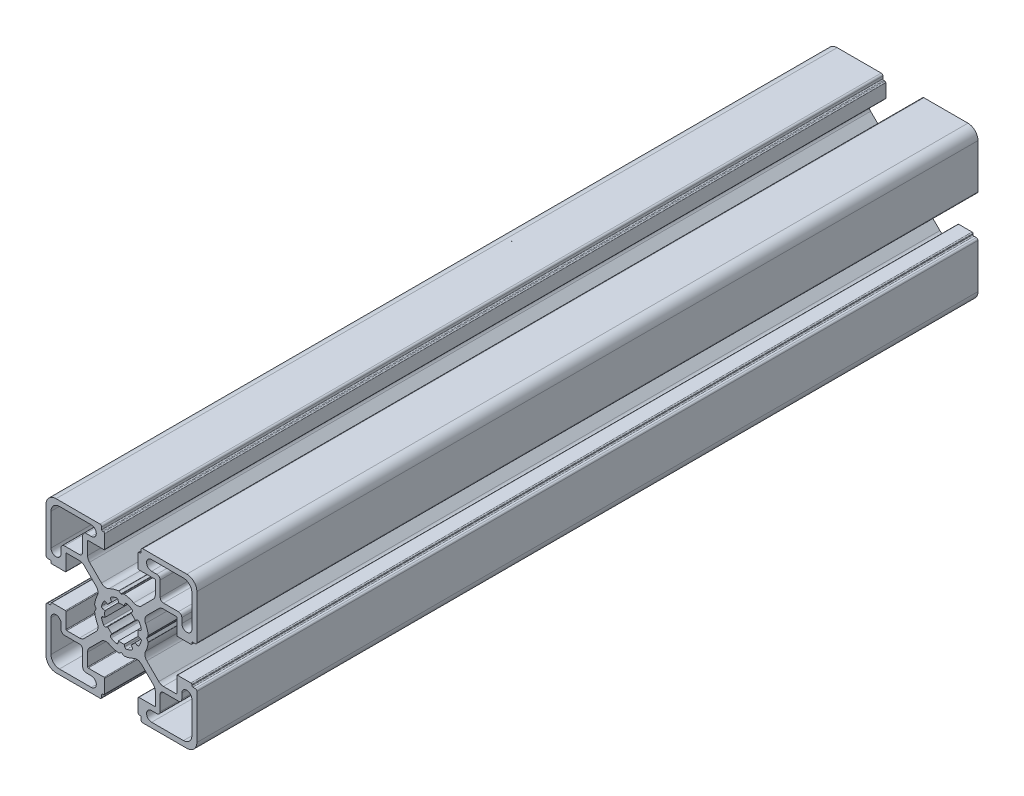
SolidWorks part; units mm, degrees
ref_plane "Front Plane" through (0, 0, 0) normal (0, 0, 1) x (1, 0, 0)
ref_plane "Top Plane" through (0, 0, 0) normal (0, 1, 0) x (1, 0, 0)
ref_plane "Right Plane" through (0, 0, 0) normal (1, 0, 0) x (0, 0, -1)
sketch "Sketch1" plane through (0, 0, 0) normal (0, 0, 1) x (1, 0, 0)
  line L0 (10.55, 18) -> (9, 18)
  line L1 (18.5, 21) -> (9, 21)
  line L2 (21, 9.0002) -> (21, 18.5)
  line L3 (18, 9.0002) -> (18, 10.55)
  line L4 (17, 11.55) -> (12.55, 11.55)
  line L5 (11.55, 12.55) -> (11.55, 17)
  line L6 (7.974, 0.7926) -> (7.5401, 0.0468)
  line L7 (-0.8674, 4.9242) -> (-0.9675, 5.4811)
  line L8 (-3.1913, 4.5626) -> (-2.864, 4.0985)
  line L9 (-4.0897, 2.8765) -> (-4.5668, 3.2082)
  line L10 (-5.4897, 0.9862) -> (-4.9205, 0.8878)
  line L11 (11.1298, 9.425) -> (7.5635, 5.8587)
  line L12 (16.3169, 9.9945) -> (12.5048, 9.9945)
  line L13 (16.5169, 5.2) -> (16.5169, 9.7945)
  line L14 (20.7196, 5) -> (16.7169, 5)
  line L15 (21.0196, 5.3) -> (21.0196, 5.5)
  line L16 (22, 5.8) -> (21.3196, 5.8)
  line L17 (22.5, 6.3) -> (22.5, 19.5)
  line L18 (19.5, 22.5) -> (6.3757, 22.5)
  line L19 (5.8757, 21.3) -> (5.8757, 22)
  line L20 (5.5757, 21) -> (5.3, 21)
  line L21 (5, 16.6668) -> (5, 20.7)
  line L22 (9.9054, 16.4668) -> (5.2, 16.4668)
  line L23 (10.1054, 12.4716) -> (10.1054, 16.2668)
  line L24 (5.9449, 7.4827) -> (9.5196, 11.0574)
  line L25 (0.1126, 7.6069) -> (0.7547, 7.9748)
  line L26 (5.4897, 0.9862) -> (4.9205, 0.8878)
  line L27 (4.0897, 2.8765) -> (4.5668, 3.2082)
  line L28 (3.1913, 4.5626) -> (2.864, 4.0985)
  line L29 (0.8674, 4.9242) -> (0.9675, 5.4811)
  line L30 (-10.55, -18) -> (-9, -18)
  line L31 (-18.5, -21) -> (-9, -21)
  line L32 (-21, -9.0002) -> (-21, -18.5)
  line L33 (-18, -9.0002) -> (-18, -10.55)
  line L34 (-17, -11.55) -> (-12.55, -11.55)
  line L35 (-11.55, -12.55) -> (-11.55, -17)
  line L36 (-7.974, -0.7926) -> (-7.5401, -0.0468)
  line L37 (-11.1298, -9.425) -> (-7.5635, -5.8587)
  line L38 (-16.3169, -9.9945) -> (-12.5048, -9.9945)
  line L39 (-16.5169, -5.2) -> (-16.5169, -9.7945)
  line L40 (-20.7196, -5) -> (-16.7169, -5)
  line L41 (-21.0196, -5.3) -> (-21.0196, -5.5)
  line L42 (-22, -5.8) -> (-21.3196, -5.8)
  line L43 (-22.5, -6.3) -> (-22.5, -19.5)
  line L44 (-19.5, -22.5) -> (-6.3757, -22.5)
  line L45 (-5.8757, -21.3) -> (-5.8757, -22)
  line L46 (-5.5757, -21) -> (-5.3, -21)
  line L47 (-5, -16.6668) -> (-5, -20.7)
  line L48 (-9.9054, -16.4668) -> (-5.2, -16.4668)
  line L49 (-10.1054, -12.4716) -> (-10.1054, -16.2668)
  line L50 (-5.9449, -7.4827) -> (-9.5196, -11.0574)
  line L51 (-0.1126, -7.6069) -> (-0.7547, -7.9748)
  line L52 (0.8674, -4.9242) -> (0.9675, -5.4811)
  line L53 (3.1913, -4.5626) -> (2.864, -4.0985)
  line L54 (4.0897, -2.8765) -> (4.5668, -3.2082)
  line L55 (5.4897, -0.9862) -> (4.9205, -0.8878)
  line L56 (0.1126, -7.6069) -> (0.7547, -7.9748)
  line L57 (5.9449, -7.4827) -> (9.5196, -11.0574)
  line L58 (10.1054, -12.4716) -> (10.1054, -16.2668)
  line L59 (9.9054, -16.4668) -> (5.2, -16.4668)
  line L60 (5, -16.6668) -> (5, -20.7)
  line L61 (5.5757, -21) -> (5.3, -21)
  line L62 (-0.1126, 7.6069) -> (-0.7547, 7.9748)
  line L63 (-5.9449, 7.4827) -> (-9.5196, 11.0574)
  line L64 (-10.1054, 12.4716) -> (-10.1054, 16.2668)
  line L65 (-9.9054, 16.4668) -> (-5.2, 16.4668)
  line L66 (-5, 16.6668) -> (-5, 20.7)
  line L67 (-5.5757, 21) -> (-5.3, 21)
  line L68 (-5.8757, 21.3) -> (-5.8757, 22)
  line L69 (-19.5, 22.5) -> (-6.3757, 22.5)
  line L70 (-22.5, 6.3) -> (-22.5, 19.5)
  line L71 (-22, 5.8) -> (-21.3196, 5.8)
  line L72 (-21.0196, 5.3) -> (-21.0196, 5.5)
  line L73 (-20.7196, 5) -> (-16.7169, 5)
  line L74 (-16.5169, 5.2) -> (-16.5169, 9.7945)
  line L75 (-16.3169, 9.9945) -> (-12.5048, 9.9945)
  line L76 (-11.1298, 9.425) -> (-7.5635, 5.8587)
  line L77 (-7.974, 0.7926) -> (-7.5401, 0.0468)
  line L78 (5.8757, -21.3) -> (5.8757, -22)
  line L79 (19.5, -22.5) -> (6.3757, -22.5)
  line L80 (22.5, -6.3) -> (22.5, -19.5)
  line L81 (22, -5.8) -> (21.3196, -5.8)
  line L82 (21.0196, -5.3) -> (21.0196, -5.5)
  line L83 (20.7196, -5) -> (16.7169, -5)
  line L84 (16.5169, -5.2) -> (16.5169, -9.7945)
  line L85 (16.3169, -9.9945) -> (12.5048, -9.9945)
  line L86 (11.1298, -9.425) -> (7.5635, -5.8587)
  line L87 (-5.4897, -0.9862) -> (-4.9205, -0.8878)
  line L88 (-4.0897, -2.8765) -> (-4.5668, -3.2082)
  line L89 (-3.1913, -4.5626) -> (-2.864, -4.0985)
  line L90 (-0.8674, -4.9242) -> (-0.9675, -5.4811)
  line L91 (7.974, -0.7926) -> (7.5401, -0.0468)
  line L92 (-11.55, 12.55) -> (-11.55, 17)
  line L93 (-17, 11.55) -> (-12.55, 11.55)
  line L94 (-18, 9.0002) -> (-18, 10.55)
  line L95 (-21, 9.0002) -> (-21, 18.5)
  line L96 (-18.5, 21) -> (-9, 21)
  line L97 (-10.55, 18) -> (-9, 18)
  line L98 (11.55, -12.55) -> (11.55, -17)
  line L99 (17, -11.55) -> (12.55, -11.55)
  line L100 (18, -9.0002) -> (18, -10.55)
  line L101 (21, -9.0002) -> (21, -18.5)
  line L102 (18.5, -21) -> (9, -21)
  line L103 (10.55, -18) -> (9, -18)
  line L104 (-33.3633, 0) -> (37.7265, 0) construction
  line L105 (0, 32.2957) -> (0, -36.0465) construction
  arc A0 (9, 18) -> (9, 21) centre (9, 19.5) cw
  arc A1 (18.5, 21) -> (21, 18.5) centre (18.5, 18.5) cw
  arc A2 (21, 9.0002) -> (18, 9.0002) centre (19.5, 9.0002) cw
  arc A3 (17, 11.55) -> (18, 10.55) centre (17, 10.55) cw
  arc A4 (12.55, 11.55) -> (11.55, 12.55) centre (12.55, 12.55) cw
  arc A5 (10.55, 18) -> (11.55, 17) centre (10.55, 17) cw
  arc A6 (7.5313, 0) -> (7.5401, 0.0468) centre (7.7309, -0.013) cw
  arc A7 (8, 0.9141) -> (7.974, 0.7926) centre (7.8011, 0.8932) cw
  arc A8 (7.2004, 3.6119) -> (8, 0.9141) centre (0.0496, 0.0249) cw
  arc A9 (7.2004, 3.6119) -> (7.5635, 5.8587) centre (8.9385, 4.4837) cw
  arc A10 (11.1298, 9.425) -> (12.5048, 9.9945) centre (12.5048, 8.05) cw
  arc A11 (16.3169, 9.9945) -> (16.5169, 9.7945) centre (16.3169, 9.7945) cw
  arc A12 (16.7169, 5) -> (16.5169, 5.2) centre (16.7169, 5.2) cw
  arc A13 (21.0196, 5.3) -> (20.7196, 5) centre (20.7196, 5.3) cw
  arc A14 (0.8674, 4.9242) -> (-0.8674, 4.9242) centre (0, 0) ccw
  arc A15 (-0.9675, 5.4811) -> (-1.5951, 5.8941) centre (-1.4627, 5.4119) ccw
  arc A16 (-1.5951, 5.8941) -> (-3.0444, 5.2994) centre (-0.0235, 0) ccw
  arc A17 (-3.0444, 5.2994) -> (-3.1913, 4.5626) centre (-2.7943, 4.8665) ccw
  arc A18 (-2.864, 4.0985) -> (-4.0897, 2.8765) centre (0, 0) ccw
  arc A19 (-4.5668, 3.2082) -> (-5.3025, 3.0565) centre (-4.868, 2.8091) ccw
  arc A20 (-5.3025, 3.0565) -> (-5.9068, 1.6112) centre (-0.0235, 0) ccw
  arc A21 (-5.9068, 1.6112) -> (-5.4897, 0.9862) centre (-5.4239, 1.4819) ccw
  arc A22 (-4.9205, 0.8878) -> (-5, 0) centre (0, 0) ccw
  arc A23 (21.0196, 5.5) -> (21.3196, 5.8) centre (21.3196, 5.5) cw
  arc A24 (22.5, 6.3) -> (22, 5.8) centre (22, 6.3) cw
  arc A25 (19.5, 22.5) -> (22.5, 19.5) centre (19.5, 19.5) cw
  arc A26 (5.8757, 22) -> (6.3757, 22.5) centre (6.3757, 22) cw
  arc A27 (5.8757, 21.3) -> (5.5757, 21) centre (5.5757, 21.3) cw
  arc A28 (5, 20.7) -> (5.3, 21) centre (5.3, 20.7) cw
  arc A29 (5.2, 16.4668) -> (5, 16.6668) centre (5.2, 16.6668) cw
  arc A30 (9.9054, 16.4668) -> (10.1054, 16.2668) centre (9.9054, 16.2668) cw
  arc A31 (10.1054, 12.4716) -> (9.5196, 11.0574) centre (8.1054, 12.4716) cw
  arc A32 (5.9449, 7.4827) -> (3.6665, 7.1733) centre (4.5855, 8.9496) cw
  arc A33 (0.8764, 8) -> (3.6665, 7.1733) centre (0.0235, 0) cw
  arc A34 (0.7547, 7.9748) -> (0.8764, 8) centre (0.8542, 7.8013) cw
  arc A35 (0.1126, 7.6069) -> (0, 7.531) centre (-0.0489, 7.7249) cw
  arc A36 (4.9205, 0.8878) -> (5, 0) centre (0, 0) cw
  arc A37 (5.9068, 1.6112) -> (5.4897, 0.9862) centre (5.4239, 1.4819) cw
  arc A38 (5.3025, 3.0565) -> (5.9068, 1.6112) centre (0.0235, 0) cw
  arc A39 (4.5668, 3.2082) -> (5.3025, 3.0565) centre (4.868, 2.8091) cw
  arc A40 (2.864, 4.0985) -> (4.0897, 2.8765) centre (0, 0) cw
  arc A41 (3.0444, 5.2994) -> (3.1913, 4.5626) centre (2.7943, 4.8665) cw
  arc A42 (1.5951, 5.8941) -> (3.0444, 5.2994) centre (0.0235, 0) cw
  arc A43 (0.9675, 5.4811) -> (1.5951, 5.8941) centre (1.4627, 5.4119) cw
  arc A44 (-9, -18) -> (-9, -21) centre (-9, -19.5) cw
  arc A45 (-18.5, -21) -> (-21, -18.5) centre (-18.5, -18.5) cw
  arc A46 (-21, -9.0002) -> (-18, -9.0002) centre (-19.5, -9.0002) cw
  arc A47 (-17, -11.55) -> (-18, -10.55) centre (-17, -10.55) cw
  arc A48 (-12.55, -11.55) -> (-11.55, -12.55) centre (-12.55, -12.55) cw
  arc A49 (-10.55, -18) -> (-11.55, -17) centre (-10.55, -17) cw
  arc A50 (-7.5313, 0) -> (-7.5401, -0.0468) centre (-7.7309, 0.013) cw
  arc A51 (-8, -0.9141) -> (-7.974, -0.7926) centre (-7.8011, -0.8932) cw
  arc A52 (-7.2004, -3.6119) -> (-8, -0.9141) centre (-0.0496, -0.0249) cw
  arc A53 (-7.2004, -3.6119) -> (-7.5635, -5.8587) centre (-8.9385, -4.4837) cw
  arc A54 (-11.1298, -9.425) -> (-12.5048, -9.9945) centre (-12.5048, -8.05) cw
  arc A55 (-16.3169, -9.9945) -> (-16.5169, -9.7945) centre (-16.3169, -9.7945) cw
  arc A56 (-16.7169, -5) -> (-16.5169, -5.2) centre (-16.7169, -5.2) cw
  arc A57 (-21.0196, -5.3) -> (-20.7196, -5) centre (-20.7196, -5.3) cw
  arc A58 (-21.0196, -5.5) -> (-21.3196, -5.8) centre (-21.3196, -5.5) cw
  arc A59 (-22.5, -6.3) -> (-22, -5.8) centre (-22, -6.3) cw
  arc A60 (-19.5, -22.5) -> (-22.5, -19.5) centre (-19.5, -19.5) cw
  arc A61 (-5.8757, -22) -> (-6.3757, -22.5) centre (-6.3757, -22) cw
  arc A62 (-5.8757, -21.3) -> (-5.5757, -21) centre (-5.5757, -21.3) cw
  arc A63 (-5, -20.7) -> (-5.3, -21) centre (-5.3, -20.7) cw
  arc A64 (-5.2, -16.4668) -> (-5, -16.6668) centre (-5.2, -16.6668) cw
  arc A65 (-9.9054, -16.4668) -> (-10.1054, -16.2668) centre (-9.9054, -16.2668) cw
  arc A66 (-10.1054, -12.4716) -> (-9.5196, -11.0574) centre (-8.1054, -12.4716) cw
  arc A67 (-5.9449, -7.4827) -> (-3.6665, -7.1733) centre (-4.5855, -8.9496) cw
  arc A68 (-0.8764, -8) -> (-3.6665, -7.1733) centre (-0.0235, 0) cw
  arc A69 (-0.7547, -7.9748) -> (-0.8764, -8) centre (-0.8542, -7.8013) cw
  arc A70 (-0.1126, -7.6069) -> (0, -7.531) centre (0.0489, -7.7249) cw
  arc A71 (0.9675, -5.4811) -> (1.5951, -5.8941) centre (1.4627, -5.4119) ccw
  arc A72 (1.5951, -5.8941) -> (3.0444, -5.2994) centre (0.0235, 0) ccw
  arc A73 (3.0444, -5.2994) -> (3.1913, -4.5626) centre (2.7943, -4.8665) ccw
  arc A74 (2.864, -4.0985) -> (4.0897, -2.8765) centre (0, 0) ccw
  arc A75 (4.5668, -3.2082) -> (5.3025, -3.0565) centre (4.868, -2.8091) ccw
  arc A76 (5.3025, -3.0565) -> (5.9068, -1.6112) centre (0.0235, 0) ccw
  arc A77 (5.9068, -1.6112) -> (5.4897, -0.9862) centre (5.4239, -1.4819) ccw
  arc A78 (4.9205, -0.8878) -> (5, 0) centre (0, 0) ccw
  arc A79 (0.1126, -7.6069) -> (0, -7.531) centre (-0.0489, -7.7249) ccw
  arc A80 (0.7547, -7.9748) -> (0.8764, -8) centre (0.8542, -7.8013) ccw
  arc A81 (0.8764, -8) -> (3.6665, -7.1733) centre (0.0235, 0) ccw
  arc A82 (5.9449, -7.4827) -> (3.6665, -7.1733) centre (4.5855, -8.9496) ccw
  arc A83 (10.1054, -12.4716) -> (9.5196, -11.0574) centre (8.1054, -12.4716) ccw
  arc A84 (9.9054, -16.4668) -> (10.1054, -16.2668) centre (9.9054, -16.2668) ccw
  arc A85 (5.2, -16.4668) -> (5, -16.6668) centre (5.2, -16.6668) ccw
  arc A86 (5, -20.7) -> (5.3, -21) centre (5.3, -20.7) ccw
  arc A87 (5.8757, -21.3) -> (5.5757, -21) centre (5.5757, -21.3) ccw
  arc A88 (-0.1126, 7.6069) -> (0, 7.531) centre (0.0489, 7.7249) ccw
  arc A89 (-0.7547, 7.9748) -> (-0.8764, 8) centre (-0.8542, 7.8013) ccw
  arc A90 (-0.8764, 8) -> (-3.6665, 7.1733) centre (-0.0235, 0) ccw
  arc A91 (-5.9449, 7.4827) -> (-3.6665, 7.1733) centre (-4.5855, 8.9496) ccw
  arc A92 (-10.1054, 12.4716) -> (-9.5196, 11.0574) centre (-8.1054, 12.4716) ccw
  arc A93 (-9.9054, 16.4668) -> (-10.1054, 16.2668) centre (-9.9054, 16.2668) ccw
  arc A94 (-5.2, 16.4668) -> (-5, 16.6668) centre (-5.2, 16.6668) ccw
  arc A95 (-5, 20.7) -> (-5.3, 21) centre (-5.3, 20.7) ccw
  arc A96 (-5.8757, 21.3) -> (-5.5757, 21) centre (-5.5757, 21.3) ccw
  arc A97 (-5.8757, 22) -> (-6.3757, 22.5) centre (-6.3757, 22) ccw
  arc A98 (-19.5, 22.5) -> (-22.5, 19.5) centre (-19.5, 19.5) ccw
  arc A99 (-22.5, 6.3) -> (-22, 5.8) centre (-22, 6.3) ccw
  arc A100 (-21.0196, 5.5) -> (-21.3196, 5.8) centre (-21.3196, 5.5) ccw
  arc A101 (-21.0196, 5.3) -> (-20.7196, 5) centre (-20.7196, 5.3) ccw
  arc A102 (-16.7169, 5) -> (-16.5169, 5.2) centre (-16.7169, 5.2) ccw
  arc A103 (-16.3169, 9.9945) -> (-16.5169, 9.7945) centre (-16.3169, 9.7945) ccw
  arc A104 (-11.1298, 9.425) -> (-12.5048, 9.9945) centre (-12.5048, 8.05) ccw
  arc A105 (-7.2004, 3.6119) -> (-7.5635, 5.8587) centre (-8.9385, 4.4837) ccw
  arc A106 (-7.2004, 3.6119) -> (-8, 0.9141) centre (-0.0496, 0.0249) ccw
  arc A107 (-8, 0.9141) -> (-7.974, 0.7926) centre (-7.8011, 0.8932) ccw
  arc A108 (-7.5313, 0) -> (-7.5401, 0.0468) centre (-7.7309, -0.013) ccw
  arc A109 (5.8757, -22) -> (6.3757, -22.5) centre (6.3757, -22) ccw
  arc A110 (19.5, -22.5) -> (22.5, -19.5) centre (19.5, -19.5) ccw
  arc A111 (22.5, -6.3) -> (22, -5.8) centre (22, -6.3) ccw
  arc A112 (21.0196, -5.5) -> (21.3196, -5.8) centre (21.3196, -5.5) ccw
  arc A113 (-4.9205, -0.8878) -> (-5, 0) centre (0, 0) cw
  arc A114 (-5.9068, -1.6112) -> (-5.4897, -0.9862) centre (-5.4239, -1.4819) cw
  arc A115 (-5.3025, -3.0565) -> (-5.9068, -1.6112) centre (-0.0235, 0) cw
  arc A116 (-4.5668, -3.2082) -> (-5.3025, -3.0565) centre (-4.868, -2.8091) cw
  arc A117 (-2.864, -4.0985) -> (-4.0897, -2.8765) centre (0, 0) cw
  arc A118 (-3.0444, -5.2994) -> (-3.1913, -4.5626) centre (-2.7943, -4.8665) cw
  arc A119 (-1.5951, -5.8941) -> (-3.0444, -5.2994) centre (-0.0235, 0) cw
  arc A120 (-0.9675, -5.4811) -> (-1.5951, -5.8941) centre (-1.4627, -5.4119) cw
  arc A121 (0.8674, -4.9242) -> (-0.8674, -4.9242) centre (0, 0) cw
  arc A122 (21.0196, -5.3) -> (20.7196, -5) centre (20.7196, -5.3) ccw
  arc A123 (16.7169, -5) -> (16.5169, -5.2) centre (16.7169, -5.2) ccw
  arc A124 (-10.55, 18) -> (-11.55, 17) centre (-10.55, 17) ccw
  arc A125 (-12.55, 11.55) -> (-11.55, 12.55) centre (-12.55, 12.55) ccw
  arc A126 (-17, 11.55) -> (-18, 10.55) centre (-17, 10.55) ccw
  arc A127 (-21, 9.0002) -> (-18, 9.0002) centre (-19.5, 9.0002) ccw
  arc A128 (-18.5, 21) -> (-21, 18.5) centre (-18.5, 18.5) ccw
  arc A129 (-9, 18) -> (-9, 21) centre (-9, 19.5) ccw
  arc A130 (16.3169, -9.9945) -> (16.5169, -9.7945) centre (16.3169, -9.7945) ccw
  arc A131 (11.1298, -9.425) -> (12.5048, -9.9945) centre (12.5048, -8.05) ccw
  arc A132 (7.2004, -3.6119) -> (7.5635, -5.8587) centre (8.9385, -4.4837) ccw
  arc A133 (7.2004, -3.6119) -> (8, -0.9141) centre (0.0496, -0.0249) ccw
  arc A134 (8, -0.9141) -> (7.974, -0.7926) centre (7.8011, -0.8932) ccw
  arc A135 (7.5313, 0) -> (7.5401, -0.0468) centre (7.7309, 0.013) ccw
  arc A136 (10.55, -18) -> (11.55, -17) centre (10.55, -17) ccw
  arc A137 (12.55, -11.55) -> (11.55, -12.55) centre (12.55, -12.55) ccw
  arc A138 (17, -11.55) -> (18, -10.55) centre (17, -10.55) ccw
  arc A139 (21, -9.0002) -> (18, -9.0002) centre (19.5, -9.0002) ccw
  arc A140 (18.5, -21) -> (21, -18.5) centre (18.5, -18.5) ccw
  arc A141 (9, -18) -> (9, -21) centre (9, -19.5) ccw
  dimension "D6" = 12.2
  dimension "D8" = 10
  dimension "D1" = 10
  dimension "D2" = 45
  dimension "D3" = 45
  dimension "D4" = 10
  dimension "D5" = 14.5
  dimension "D7" = 22.5
extrude "Base-Extrude" add sketch "Sketch1" against normal blind 360
sketch "Sketch2" plane through (22.5, 0, 0) normal (1, 0, 0) x (0, 0, -1)
  line L0 (0, 6.3) -> (0, 19.5) construction
  circle A0 centre (85, 0) radius 4.2
  circle A1 centre (45, 0) radius 4.2
  dimension "D1" = 85
  dimension "D2" = 40
extrude "Cut-Extrude1" cut sketch "Sketch2" against normal blind 164
sketch "Sketch3" plane through (0, 0, 0) normal (0, 0, 1) x (1, 0, 0)
  line L1 (-35.4211, 28.4896) -> (43.5274, 28.4896)
  line L2 (-35.4211, 28.4896) -> (-35.4211, -42.0001)
  line L3 (-35.4211, -42.0001) -> (43.5274, -42.0001)
  line L4 (43.5274, 28.4896) -> (43.5274, -42.0001)
extrude "Cut-Extrude2" cut sketch "Sketch3" against normal blind 127
